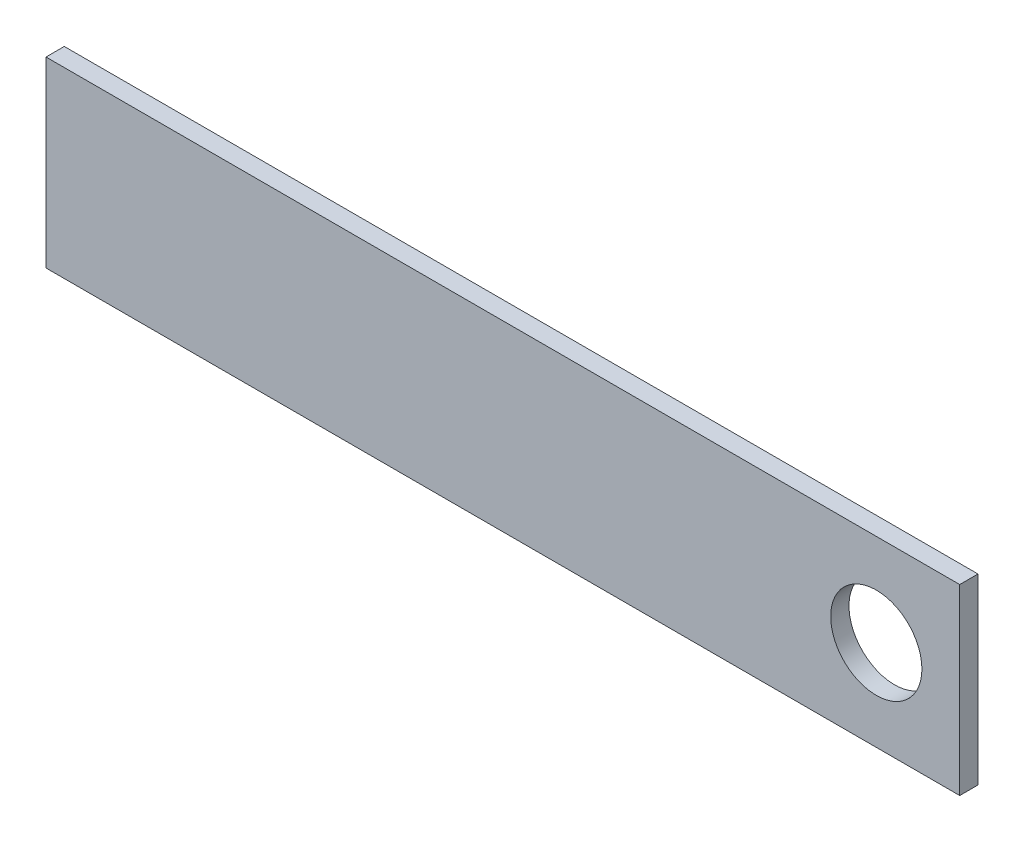
SolidWorks part; units mm, degrees
ref_plane "Front Plane" through (0, 0, 0) normal (0, 0, 1) x (1, 0, 0)
ref_plane "Top Plane" through (0, 0, 0) normal (0, 1, 0) x (1, 0, 0)
ref_plane "Right Plane" through (0, 0, 0) normal (1, 0, 0) x (0, 0, -1)
sketch "Sketch1" plane through (0, 0, 0) normal (0, 1, 0) x (1, 0, 0)
  line L1 (0, 0) -> (100, 0)
  line L2 (0, 0) -> (0, 2)
  line L3 (0, 2) -> (100, 2)
  line L4 (100, 0) -> (100, 2)
  dimension "D1" = 100
  dimension "D2" = 2
extrude "Boss-Extrude1" add sketch "Sketch1" along normal blind 20
sketch "Sketch3" plane through (0, 0, 0) normal (0, 0, 1) x (1, 0, 0)
  circle A0 centre (90.8701, 9.9197) radius 4.9913
  point P4 (0, 10)
extrude "Cut-Extrude1" cut sketch "Sketch3" against normal through all
